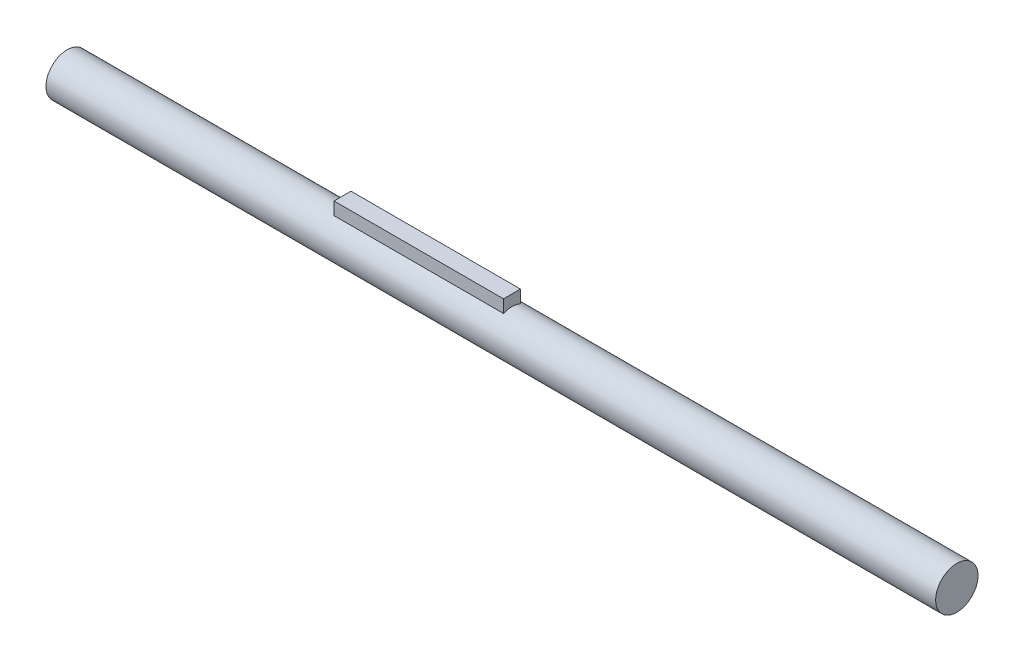
SolidWorks part; units mm, degrees
ref_plane "Front Plane" through (0, 0, 0) normal (0, 0, 1) x (1, 0, 0)
ref_plane "Top Plane" through (0, 0, 0) normal (0, 1, 0) x (1, 0, 0)
ref_plane "Right Plane" through (0, 0, 0) normal (1, 0, 0) x (0, 0, -1)
sketch "Sketch1" plane through (0, 0, 0) normal (1, 0, 0) x (0, 0, -1)
  circle A0 centre (0, 0) radius 25
  dimension "D1" = 50
extrude "Boss-Extrude1" add sketch "Sketch1" along normal blind 1050
ref_plane "Plane1" through (325, 0, 0) normal (-1, 0, 0) x (0, 0, 1)
sketch "Sketch2" plane through (325, 0, 0) normal (-1, 0, 0) x (0, 0, 1)
  line L0 (-10, 37.9129) -> (10, 37.9129)
  line L1 (10, 37.9129) -> (10, 22.9129)
  line L2 (-10, 22.9129) -> (-10, 37.9129)
  line L3 (-10, 22.9129) -> (10, 22.9129)
  circle A0 centre (0, 0) radius 25 construction
  point P3 (0, 37.9129)
  dimension "D1" = 20
  dimension "D2" = 15
extrude "Boss-Extrude2" add sketch "Sketch2" against normal blind 200
